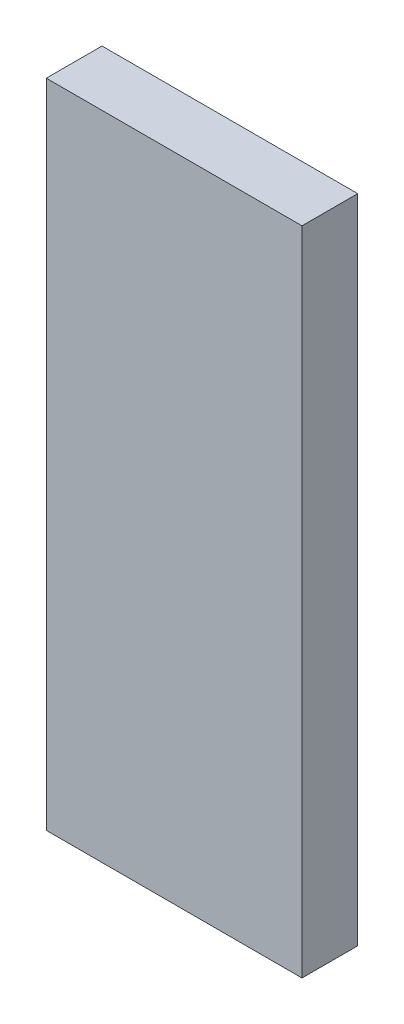
SolidWorks part; units mm, degrees
ref_plane "Front Plane" through (0, 0, 0) normal (0, 0, 1) x (1, 0, 0)
ref_plane "Top Plane" through (0, 0, 0) normal (0, 1, 0) x (1, 0, 0)
ref_plane "Right Plane" through (0, 0, 0) normal (1, 0, 0) x (0, 0, -1)
sketch "Sketch1" plane through (0, 0, 0) normal (0, 0, 1) x (1, 0, 0)
  line L1 (-21.7182, 31.0897) -> (10.4018, 31.0897)
  line L2 (-21.7182, 31.0897) -> (-21.7182, -50.7375)
  line L3 (-21.7182, -50.7375) -> (10.4018, -50.7375)
  line L4 (10.4018, 31.0897) -> (10.4018, -50.7375)
  dimension "D1" = 32.12
  dimension "D2" = 81.8273
extrude "Boss-Extrude1" add sketch "Sketch1" along normal blind 7
